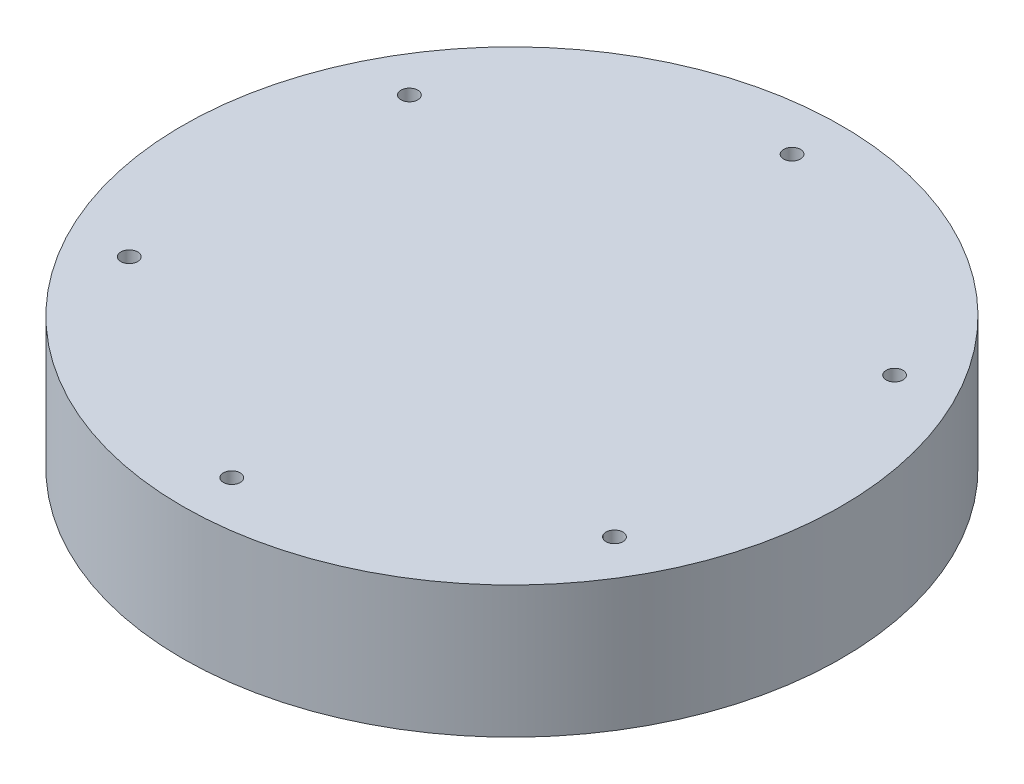
SolidWorks part; units mm, degrees
material "AISI 1020"
ref_plane "Front Plane" through (0, 0, 0) normal (0, 0, 1) x (1, 0, 0)
ref_plane "Top Plane" through (0, 0, 0) normal (0, 1, 0) x (1, 0, 0)
ref_plane "Right Plane" through (0, 0, 0) normal (1, 0, 0) x (0, 0, -1)
sketch "Sketch1" plane through (0, 0, 0) normal (0, 1, 0) x (1, 0, 0)
  circle A0 centre (0, 0) radius 100
  dimension "D1" = 200
extrude "Boss-Extrude1" add sketch "Sketch1" along normal blind 40
hole_wizard "1/4-20 Tapped Hole1" positions "Sketch3" profile "Sketch2" tap size "1/4-20" standard "ANSI Inch"
sketch "Sketch3" plane through (0, 40, 0) normal (0, 1, 0) x (1, 0, 0)
  line L0 (0, 0) -> (0, 85) construction
  line L2 (0, 85) -> (0, 100) construction
  circle A0 centre (0, 0) radius 100 construction
  point P0 (0, 85)
  dimension "D1" = 15
sketch "Sketch2" plane through (0, 40, -85) normal (1, 0, 0) x (0, 0, 1)
  line L0 (0, 0) -> (0, 18.0438)
  line L1 (0, 18.0438) -> (2.5527, 16.51)
  line L2 (2.5527, 16.51) -> (2.5527, 0)
  line L5 (2.5527, 0) -> (0, 0)
  line L10 (0, 18.0438) -> (-2.5527, 16.51) construction
  line L11 (0, -6.35) -> (0, 107.95) construction
  dimension "Tap Drill Dia." = 5.1054
  dimension "Tap Drill Depth" = 16.51
  dimension "Drill Angle" = 118
cosmetic thread "Hole Thread1" parameters "D1"=12.7, "D2"=6.35
pattern_circular "CirPattern1" count 6 over 360 about axis through (0, 0, 0) along (0, 1, 0) of "1/4-20 Tapped Hole1"
